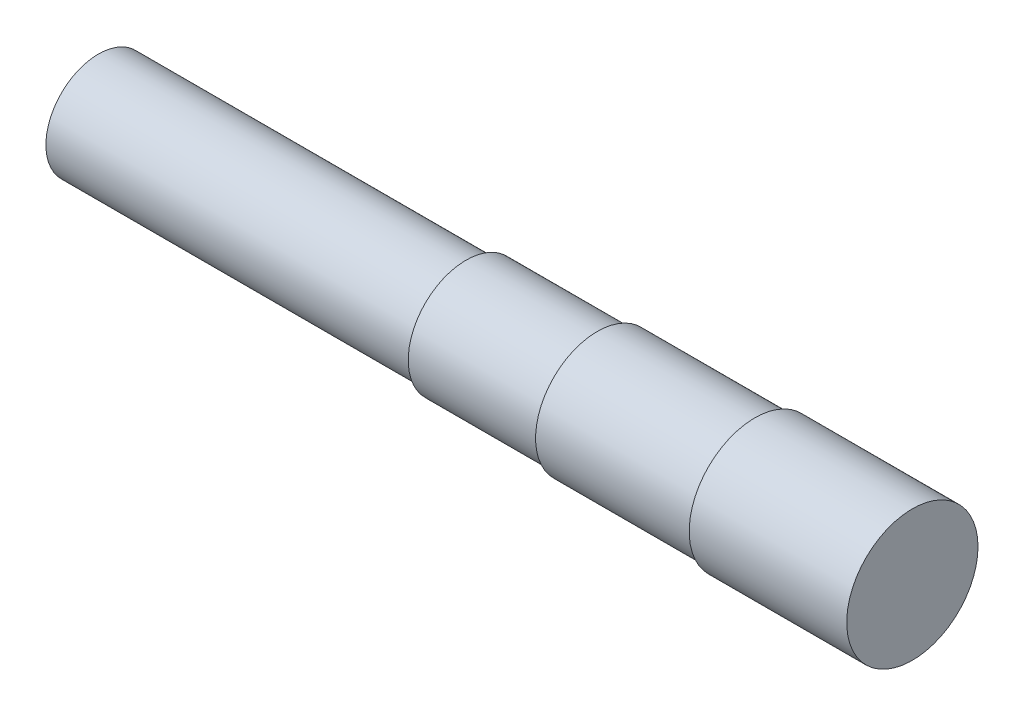
SolidWorks part; units mm, degrees
ref_plane "Front Plane" through (0, 0, 0) normal (0, 0, 1) x (1, 0, 0)
ref_plane "Top Plane" through (0, 0, 0) normal (0, 1, 0) x (1, 0, 0)
ref_plane "Right Plane" through (0, 0, 0) normal (1, 0, 0) x (0, 0, -1)
sketch "Sketch1" plane through (0, 0, 0) normal (0, 0, 1) x (1, 0, 0)
  line L1 (0, 0) -> (30, 0)
  line L2 (0, 11) -> (0, 12.5)
  line L3 (0, 12.5) -> (30, 12.5)
  line L4 (30, 0) -> (30, 12.5)
  line L5 (0, 11) -> (-55, 11)
  line L7 (0, 0) -> (-32.6087, 0)
  line L8 (-55, 11) -> (-55, 10)
  line L9 (-55, 10) -> (-125, 10)
  line L11 (-32.6087, 0) -> (-125, 0)
  line L12 (-125, 10) -> (-125, 0)
  line L13 (0, 11) -> (-30, 11)
  line L14 (0, 11) -> (0, 11.75)
  line L15 (0, 11.75) -> (-30, 11.75)
  line L16 (-30, 11) -> (-30, 11.75)
  dimension "D1" = 12.5
  dimension "D2" = 11
  dimension "D3" = 10
  dimension "D4" = 70
  dimension "D5" = 55
  dimension "D6" = 30
  dimension "D7" = 30
  dimension "D8" = 0.75
  dimension "D9" = 30
revolve "Revolve1" add sketch "Sketch1" angle 360 about L7
